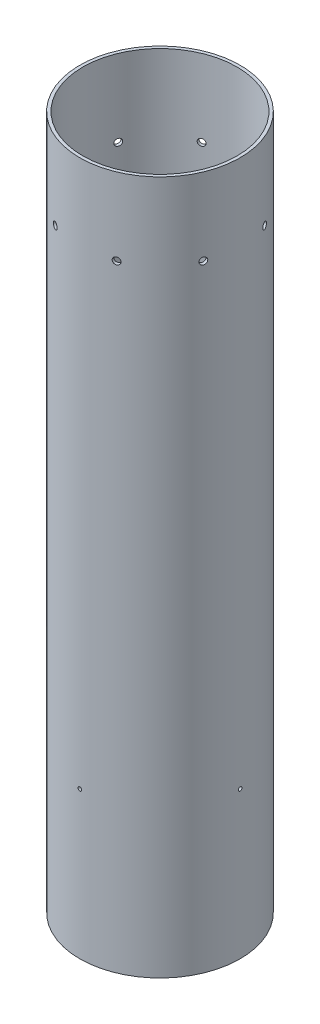
SolidWorks part; units mm, degrees
material "Corrugated Paper"
ref_plane "Front Plane" through (0, 0, 0) normal (0, 0, 1) x (1, 0, 0)
ref_plane "Top Plane" through (0, 0, 0) normal (0, 1, 0) x (1, 0, 0)
ref_plane "Right Plane" through (0, 0, 0) normal (1, 0, 0) x (0, 0, -1)
sketch "Sketch1" plane through (0, 0, 0) normal (0, 1, 0) x (1, 0, 0)
  circle A0 centre (0, 0) radius 52.832
  circle A1 centre (0, 0) radius 50.8
  dimension "D1" = 105.664
  dimension "D2" = 101.6
extrude "Boss-Extrude1" add sketch "Sketch1" along normal blind 457.2
ref_plane "Plane1" through (0, 0, 52.832) normal (0, 0, 1) x (1, 0, 0)
hole_wizard "#2 Clearance Hole1" positions "Sketch3" profile "Sketch4" hole size "#2" standard "ANSI Inch"
sketch "Sketch3" plane through (0, 0, 52.832) normal (0, 0, 1) x (1, 0, 0)
  point P0 (0, 96.9772)
  dimension "D1" = 96.9772
sketch "Sketch4" plane through (0, 96.9772, 52.832) normal (1, 0, 0) x (0, -1, 0)
  line L0 (0, 0) -> (0, 55.5966)
  line L1 (0, 55.5966) -> (1.2192, 54.864)
  line L2 (1.2192, 54.864) -> (1.2192, 0)
  line L5 (1.2192, 0) -> (0, 0)
  line L10 (0, 55.5966) -> (-1.2192, 54.864) construction
  line L11 (0, -6.35) -> (0, 107.95) construction
  dimension "Hole Dia." = 2.4384
  dimension "Hole Depth" = 54.864
  dimension "Drill Angle" = 118
ref_plane "Plane2" through (20.2179, 0, 48.8104) normal (0.3827, 0, 0.9239) x (0, -1, 0)
hole_wizard "#8 Clearance Hole1" positions "Sketch5" profile "Sketch6" hole size "#8" standard "ANSI Inch"
sketch "Sketch5" plane through (20.2179, 0, 48.8104) normal (0.3827, 0, 0.9239) x (0, -1, 0)
  line L0 (-457.2, 52.832) -> (-457.2, -52.832) construction
  point P0 (-406.4, 0)
  dimension "D1" = 50.8
sketch "Sketch6" plane through (20.2179, 406.4, 48.8104) normal (0, 1, 0) x (0.9239, 0, -0.3827)
  line L0 (0, 0) -> (0, 56.2147)
  line L1 (0, 56.2147) -> (2.2479, 54.864)
  line L2 (2.2479, 54.864) -> (2.2479, 0)
  line L5 (2.2479, 0) -> (0, 0)
  line L10 (0, 56.2147) -> (-2.2479, 54.864) construction
  line L11 (0, -6.35) -> (0, 107.95) construction
  dimension "Hole Dia." = 4.4958
  dimension "Hole Depth" = 54.864
  dimension "Drill Angle" = 118
pattern_circular "CirPattern1" count 4 over 360 about axis through (0, 457.2, 0) along (0, -1, 0) of "#2 Clearance Hole1"
pattern_circular "CirPattern2" count 8 over 360 about axis through (0, 457.2, 0) along (0, -1, 0) of "#8 Clearance Hole1"
